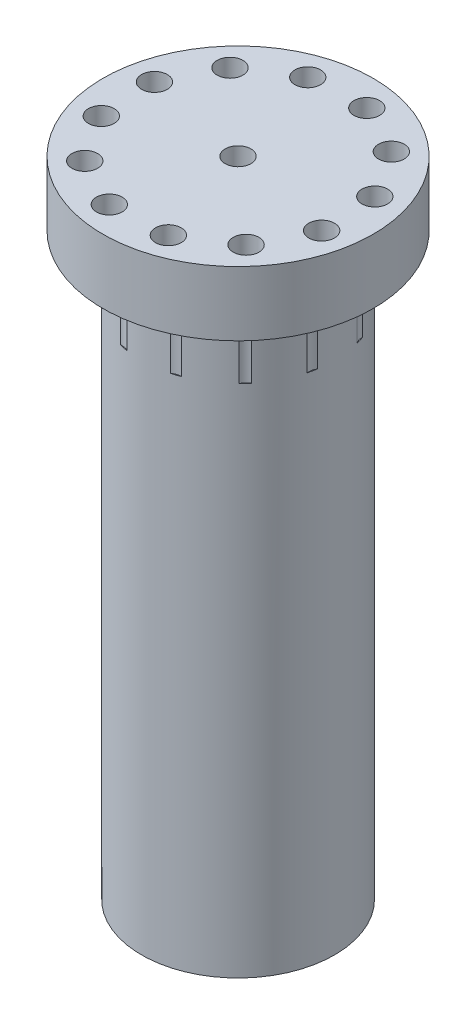
SolidWorks part; units mm, degrees
ref_plane "Front Plane" through (0, 0, 0) normal (0, 0, 1) x (1, 0, 0)
ref_plane "Top Plane" through (0, 0, 0) normal (0, 1, 0) x (1, 0, 0)
ref_plane "Right Plane" through (0, 0, 0) normal (1, 0, 0) x (0, 0, -1)
sketch "Sketch1" plane through (0, 0, 0) normal (0, 0, 1) x (1, 0, 0)
  line L0 (0, 0) -> (0, 3)
  line L1 (0, 50) -> (7.5, 50)
  line L2 (7.5, 45) -> (7.5, 0)
  line L3 (7.5, 0) -> (0, 0)
  line L4 (7.5, 50) -> (10.5, 50)
  line L5 (10.5, 50) -> (10.5, 45)
  line L6 (10.5, 45) -> (7.5, 45)
  line L7 (0, 3) -> (4.1, 3)
  line L8 (4.1, 3) -> (4.1, 18)
  line L9 (4.1, 18) -> (0, 18)
  line L10 (0, 18) -> (0, 50)
  dimension "D1" = 50
  dimension "D2" = 5
  dimension "D3" = 7.5
  dimension "D4" = 3
  dimension "D5" = 7.5
  dimension "D6" = 4.1
  dimension "D7" = 15
  dimension "D8" = 3
revolve "Revolve1" add sketch "Sketch1" angle 360 about L10
sketch "Sketch2" plane through (0, 50, 0) normal (0, 1, 0) x (1, 0, 0)
  circle A0 centre (-2.606, 8.0217) radius 1
  circle A1 centre (1.754, 8.25) radius 1
  circle A2 centre (5.644, 6.2677) radius 1
  circle A3 centre (8.0217, 2.606) radius 1
  circle A4 centre (8.25, -1.754) radius 1
  circle A5 centre (6.2677, -5.644) radius 1
  circle A6 centre (2.606, -8.0217) radius 1
  circle A7 centre (-1.754, -8.25) radius 1
  circle A8 centre (-5.644, -6.2677) radius 1
  circle A9 centre (-8.0217, -2.606) radius 1
  circle A10 centre (-8.25, 1.754) radius 1
  circle A11 centre (-6.2677, 5.644) radius 1
  circle A12 centre (0, 0) radius 10.5 construction
  point P27 (0, 0)
  dimension "D1" = 2
  dimension "D3" = 8.25
  dimension "D2" = 12
extrude "Cut-Extrude1" cut sketch "Sketch2" against normal blind 10
sketch "Sketch3" plane through (0, 0, 0) normal (0, -1, 0) x (1, 0, 0)
  circle A0 centre (0, 0) radius 3
  dimension "D1" = 6
extrude "Cut-Extrude3" cut sketch "Sketch3" against normal blind 10
sketch "Sketch4" plane through (0, 50, 0) normal (0, 1, 0) x (1, 0, 0)
  circle A0 centre (0, 0) radius 1
  dimension "D1" = 2
extrude "Cut-Extrude4" cut sketch "Sketch4" against normal through all
